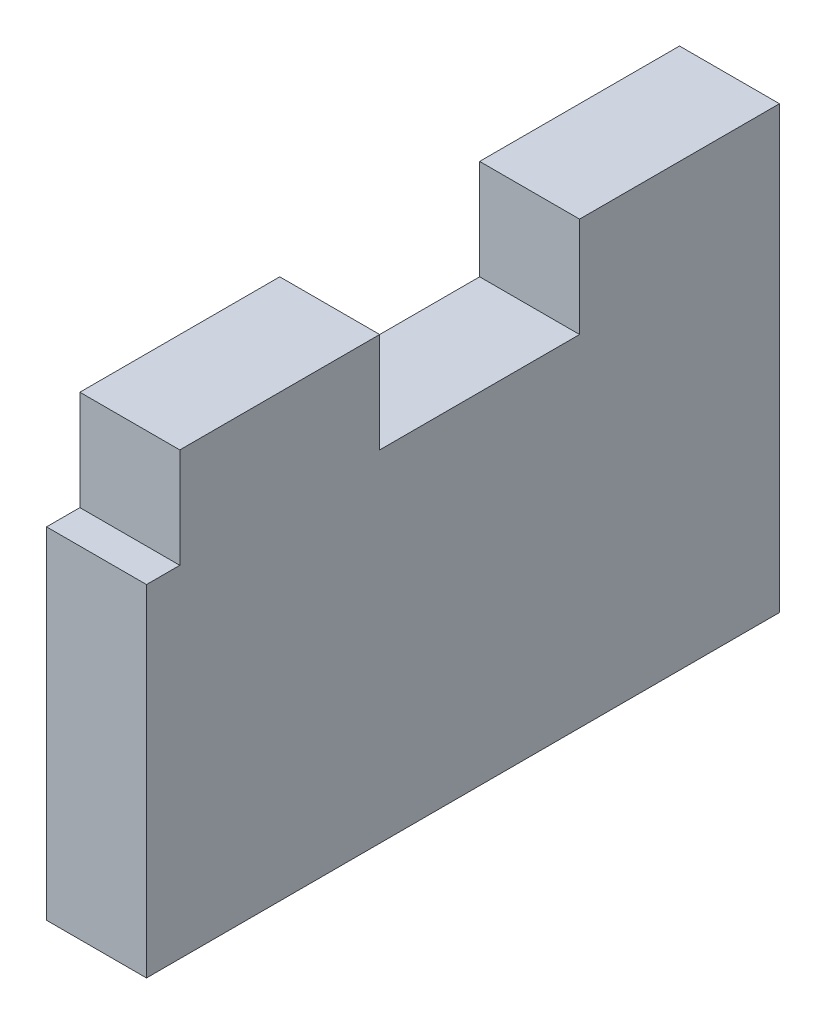
SolidWorks part; units mm, degrees
ref_plane "Front Plane" through (0, 0, 0) normal (0, 0, 1) x (1, 0, 0)
ref_plane "Top Plane" through (0, 0, 0) normal (0, 1, 0) x (1, 0, 0)
ref_plane "Right Plane" through (0, 0, 0) normal (1, 0, 0) x (0, 0, -1)
sketch "Sketch1" plane through (0, 0, 0) normal (1, 0, 0) x (0, 0, -1)
  line L0 (41.275, 41.9999) -> (60.325, 41.9999)
  line L1 (0, 0) -> (60.325, 0)
  line L2 (0, 0) -> (0, 32.4749)
  line L3 (3.175, 41.9999) -> (22.225, 41.9999)
  line L4 (60.325, 0) -> (60.325, 41.9999)
  line L7 (0, 32.4749) -> (3.175, 32.4749)
  line L8 (3.175, 41.9999) -> (3.175, 32.4749)
  line L9 (22.225, 32.4749) -> (41.275, 32.4749)
  line L10 (22.225, 32.4749) -> (22.225, 41.9999)
  line L12 (41.275, 32.4749) -> (41.275, 41.9999)
  dimension "D1" = 19.05
  dimension "D2" = 41.9999
  dimension "D3" = 9.525
  dimension "D4" = 3.175
  dimension "D5" = 19.05
  dimension "D6" = 19.05
extrude "Boss-Extrude1" add sketch "Sketch1" along normal blind 9.525
